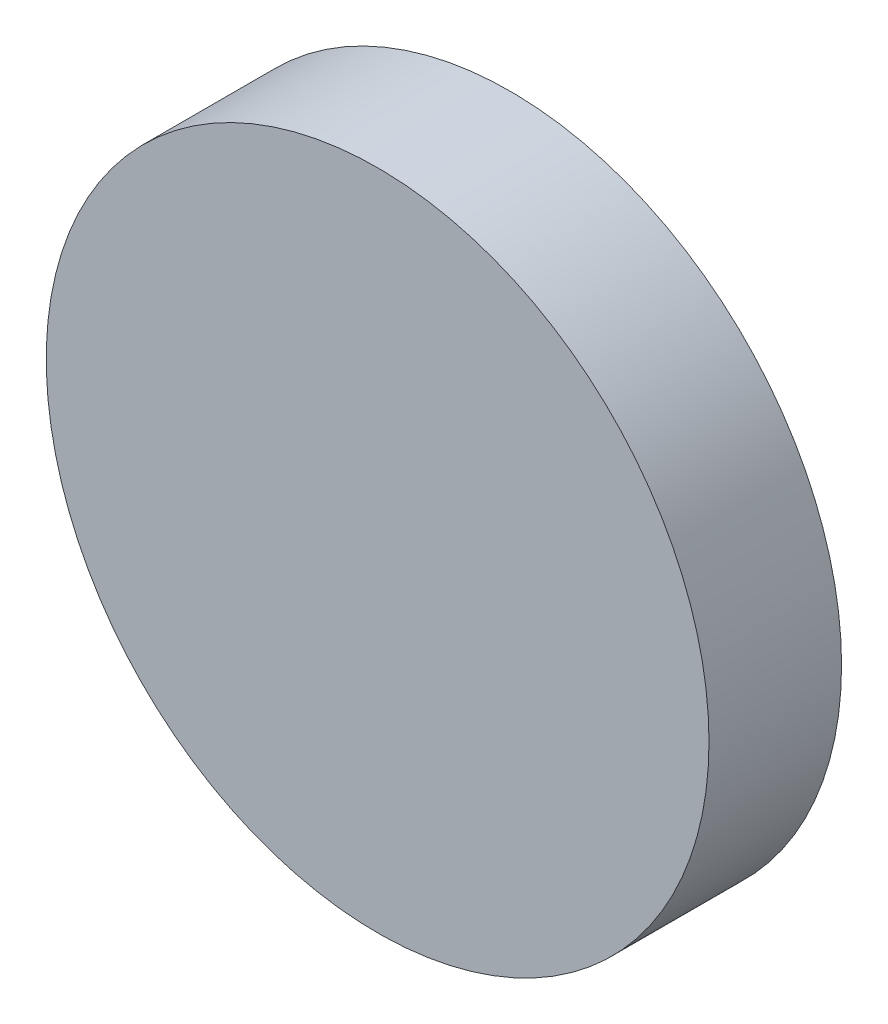
SolidWorks part; units mm, degrees
material "Silicon Dioxide"
ref_plane "Front Plane" through (0, 0, 0) normal (0, 0, 1) x (1, 0, 0)
ref_plane "Top Plane" through (0, 0, 0) normal (0, 1, 0) x (1, 0, 0)
ref_plane "Right Plane" through (0, 0, 0) normal (1, 0, 0) x (0, 0, -1)
sketch "Sketch1" plane through (0, 0, 0) normal (0, 0, 1) x (1, 0, 0)
  circle A0 centre (0, 0) radius 12.5
  dimension "D1" = 25
extrude "Boss-Extrude1" add sketch "Sketch1" along normal blind 5
